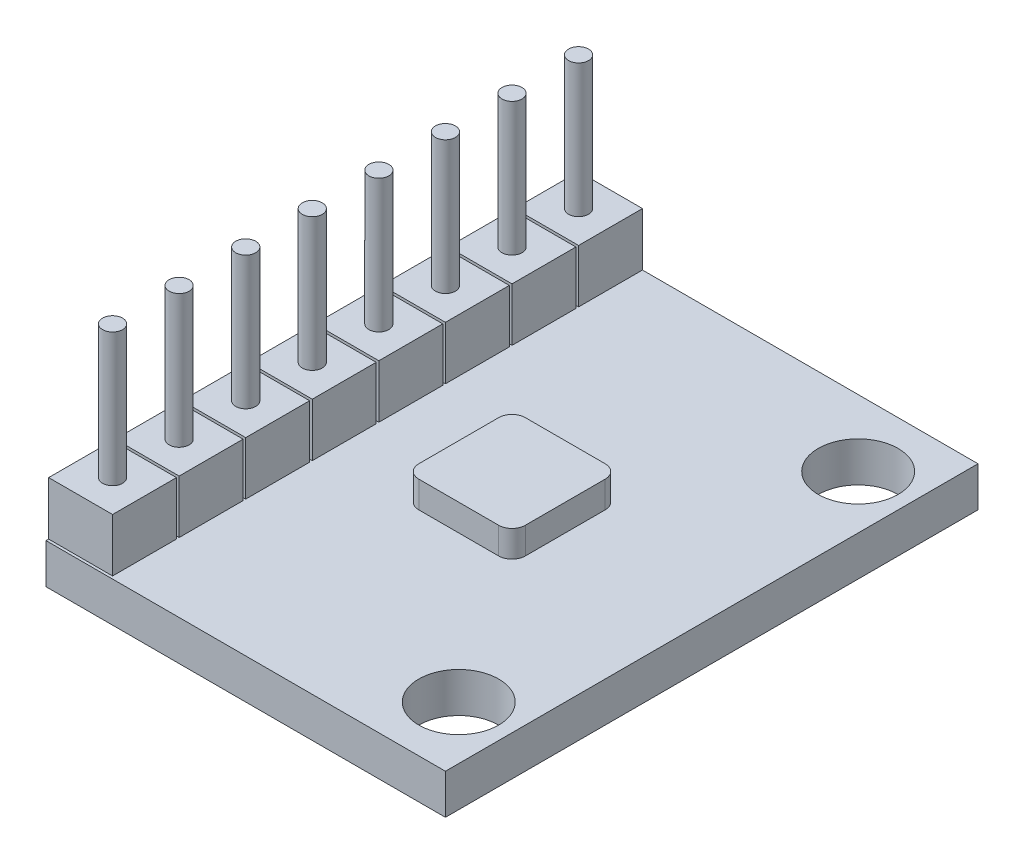
SolidWorks part; units mm, degrees
ref_plane "Front Plane" through (0, 0, 0) normal (0, 0, 1) x (1, 0, 0)
ref_plane "Top Plane" through (0, 0, 0) normal (0, 1, 0) x (1, 0, 0)
ref_plane "Right Plane" through (0, 0, 0) normal (1, 0, 0) x (0, 0, -1)
sketch "Sketch1" plane through (0, 0, 0) normal (0, 1, 0) x (1, 0, 0)
  line L1 (7.5, -10) -> (-7.5, -10)
  line L2 (7.5, -10) -> (7.5, 10)
  line L3 (7.5, 10) -> (-7.5, 10)
  line L4 (-7.5, -10) -> (-7.5, 10)
  line L5 (7.5, -10) -> (-7.5, 10) construction
  line L6 (7.5, 10) -> (-7.5, -10) construction
  point P0 (0, 0)
  dimension "D1" = 15
  dimension "D2" = 20
extrude "Boss-Extrude1" add sketch "Sketch1" along normal blind 1.5
sketch "Sketch2" plane through (0, 1.5, 0) normal (0, 1, 0) x (1, 0, 0)
  line L0 (7.5, -10) -> (7.5, 10) construction
  line L1 (-7.5, -10) -> (7.5, -10) construction
  line L2 (0, 0) -> (7.5, 0) construction
  circle A0 centre (5.5, -7.5) radius 1.5
  circle A1 centre (5.5, 7.5) radius 1.5
  dimension "D1" = 3
  dimension "D2" = 2
  dimension "D3" = 2.5
extrude "Cut-Extrude1" cut sketch "Sketch2" against normal through all
sketch "Sketch3" plane through (0, 1.5, 0) normal (0, 1, 0) x (1, 0, 0)
  line L1 (2, -2) -> (-2, -2)
  line L2 (2, -2) -> (2, 2)
  line L3 (2, 2) -> (-2, 2)
  line L4 (-2, -2) -> (-2, 2)
  line L5 (2, -2) -> (-2, 2) construction
  line L6 (2, 2) -> (-2, -2) construction
  point P0 (0, 0)
  dimension "D1" = 4
  dimension "5" = 4
extrude "Boss-Extrude2" add sketch "Sketch3" along normal blind 1
fillet "Fillet2" radius 0.5 4 edges at (-2, 2, -2) (2, 2, -2) (2, 2, 2) (-2, 2, 2)
sketch "Sketch4" plane through (0, 1.5, 0) normal (0, 1, 0) x (1, 0, 0)
  line L0 (7.5, 10) -> (-7.5, 10) construction
  line L1 (-7.5, 10) -> (-5.1, 10)
  line L2 (-7.5, 10) -> (-7.5, 7.6)
  line L3 (-7.5, 7.6) -> (-5.1, 7.6)
  line L4 (-5.1, 10) -> (-5.1, 7.6)
  line L5 (-7.5, 10) -> (-5.1, 7.6) construction
  line L6 (-7.5, 7.6) -> (-5.1, 10) construction
  line L7 (-7.5, 10) -> (-7.5, -10) construction
  line L8 (-7.5, 7.5) -> (-5.1, 7.5)
  line L9 (-5.1, 7.5) -> (-5.1, 5.1)
  line L10 (-7.5, 5.1) -> (-5.1, 5.1)
  line L11 (-7.5, 7.5) -> (-7.5, 5.1)
  line L12 (-7.5, 5) -> (-5.1, 5)
  line L13 (-5.1, 5) -> (-5.1, 2.6)
  line L14 (-7.5, 2.6) -> (-5.1, 2.6)
  line L15 (-7.5, 5) -> (-7.5, 2.6)
  line L16 (-7.5, 2.5) -> (-5.1, 2.5)
  line L17 (-5.1, 2.5) -> (-5.1, 0.1)
  line L18 (-7.5, 0.1) -> (-5.1, 0.1)
  line L19 (-7.5, 2.5) -> (-7.5, 0.1)
  line L20 (-7.5, 0) -> (-5.1, 0)
  line L21 (-5.1, 0) -> (-5.1, -2.4)
  line L22 (-7.5, -2.4) -> (-5.1, -2.4)
  line L23 (-7.5, 0) -> (-7.5, -2.4)
  line L24 (-7.5, -2.5) -> (-5.1, -2.5)
  line L25 (-5.1, -2.5) -> (-5.1, -4.9)
  line L26 (-7.5, -4.9) -> (-5.1, -4.9)
  line L27 (-7.5, -2.5) -> (-7.5, -4.9)
  line L28 (-7.5, -5) -> (-5.1, -5)
  line L29 (-5.1, -5) -> (-5.1, -7.4)
  line L30 (-7.5, -7.4) -> (-5.1, -7.4)
  line L31 (-7.5, -5) -> (-7.5, -7.4)
  line L32 (-7.5, -7.5) -> (-5.1, -7.5)
  line L33 (-5.1, -7.5) -> (-5.1, -9.9)
  line L34 (-7.5, -9.9) -> (-5.1, -9.9)
  line L35 (-7.5, -7.5) -> (-7.5, -9.9)
  point P0 (-6.3, 8.8)
  dimension "D1" = 2.4
  dimension "D2" = 2.4
  dimension "D3" = 0
  dimension "D4" = 0
  dimension "D5" = 8
extrude "Boss-Extrude3" add sketch "Sketch4" along normal blind 2
sketch "Sketch5" plane through (0, 3.5, 0) normal (0, 1, 0) x (1, 0, 0)
  line L0 (-7.5, 10) -> (-7.5, 7.6) construction
  line L1 (-5.1, 10) -> (-7.5, 10) construction
  circle A0 centre (-6.3, 8.8) radius 0.375
  circle A1 centre (-6.3, 6.3) radius 0.375
  circle A2 centre (-6.3, 3.8) radius 0.375
  circle A3 centre (-6.3, 1.3) radius 0.375
  circle A4 centre (-6.3, -1.2) radius 0.375
  circle A5 centre (-6.3, -3.7) radius 0.375
  circle A6 centre (-6.3, -6.2) radius 0.375
  circle A7 centre (-6.3, -8.7) radius 0.375
  dimension "D1" = 0.75
  dimension "D2" = 1.2
  dimension "D3" = 1.2
  dimension "D4" = 8
extrude "Boss-Extrude4" add sketch "Sketch5" along normal blind 5
